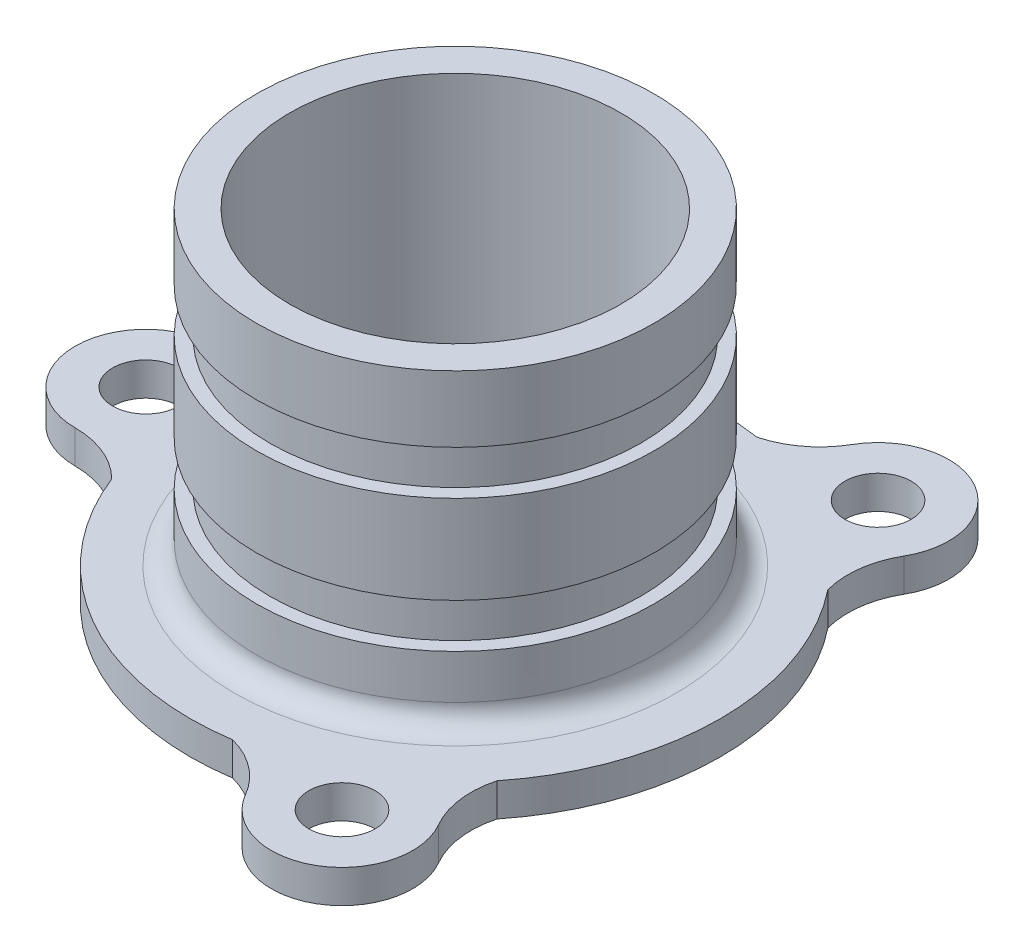
SolidWorks part; units mm, degrees
ref_plane "Front Plane" through (0, 0, 0) normal (0, 0, 1) x (1, 0, 0)
ref_plane "Top Plane" through (0, 0, 0) normal (0, 1, 0) x (1, 0, 0)
ref_plane "Right Plane" through (0, 0, 0) normal (1, 0, 0) x (0, 0, -1)
sketch "Sketch2" plane through (0, 0, 0) normal (0, 1, 0) x (1, 0, 0)
  line L1 (-70.05, 0) -> (161.6147, 0) construction
  line L2 (0, 87.4418) -> (0, -104.1606) construction
  circle A0 centre (0, 0) radius 37.5
  arc A1 (8.9547, 59.328) -> (-55.8569, 21.909) centre (0, 0) ccw
  circle A3 centre (-70.05, 0) radius 7.5
  arc A4 (-70.05, 16) -> (-70.05, -16) centre (-70.05, 0) ccw
  arc A5 (-70.05, -16) -> (-55.8569, -21.909) centre (-70.05, -36) cw
  arc A6 (-70.05, 16) -> (-55.8569, 21.909) centre (-70.05, 36) ccw
  arc A7 (48.8814, 52.6651) -> (21.1686, 68.6651) centre (35.025, 60.6651) ccw
  circle A8 centre (35.025, 60.6651) radius 7.5
  arc A9 (21.1686, 68.6651) -> (8.9547, 59.328) centre (3.8481, 78.6651) cw
  arc A10 (48.8814, 52.6651) -> (46.9022, 37.419) centre (66.2019, 42.6651) ccw
  arc A11 (21.1686, -68.6651) -> (48.8814, -52.6651) centre (35.025, -60.6651) ccw
  circle A12 centre (35.025, -60.6651) radius 7.5
  arc A13 (48.8814, -52.6651) -> (46.9022, -37.419) centre (66.2019, -42.6651) cw
  arc A14 (21.1686, -68.6651) -> (8.9547, -59.328) centre (3.8481, -78.6651) ccw
  arc A15 (46.9022, -37.419) -> (46.9022, 37.419) centre (0, 0) ccw
  arc A16 (-55.8569, -21.909) -> (8.9547, -59.328) centre (0, 0) ccw
  point P34 (0, 0)
  dimension "D1" = 75
  dimension "D2" = 120
  dimension "D3" = 3
  dimension "D4" = 15
  dimension "D5" = 32
  dimension "D6" = 20
  dimension "D7" = 20
extrude "Boss-Extrude1" add sketch "Sketch2" along normal blind 7.5
sketch "Sketch3" plane through (0, 7.5, 0) normal (0, 1, 0) x (1, 0, 0)
  circle A0 centre (0, 0) radius 37.5 construction
  circle A1 centre (0, 0) radius 37.5
  circle A2 centre (0, 0) radius 45
  arc A14 (-55.8569, -21.909) -> (-70.05, -16) centre (-70.05, -36) ccw
  arc A15 (-55.8569, -21.909) -> (8.9547, -59.328) centre (0, 0) ccw
  arc A16 (21.1686, -68.6651) -> (8.9547, -59.328) centre (3.8481, -78.6651) ccw
  arc A17 (21.1686, -68.6651) -> (48.8814, -52.6651) centre (35.025, -60.6651) ccw
  arc A18 (46.9022, -37.419) -> (48.8814, -52.6651) centre (66.2019, -42.6651) ccw
  arc A19 (46.9022, -37.419) -> (46.9022, 37.419) centre (0, 0) ccw
  arc A20 (48.8814, 52.6651) -> (46.9022, 37.419) centre (66.2019, 42.6651) ccw
  arc A21 (48.8814, 52.6651) -> (21.1686, 68.6651) centre (35.025, 60.6651) ccw
  arc A22 (8.9547, 59.328) -> (21.1686, 68.6651) centre (3.8481, 78.6651) ccw
  arc A23 (8.9547, 59.328) -> (-55.8569, 21.909) centre (0, 0) ccw
  arc A24 (-70.05, 16) -> (-55.8569, 21.909) centre (-70.05, 36) ccw
  arc A25 (-70.05, 16) -> (-70.05, -16) centre (-70.05, 0) ccw
  arc A26 (-55.8569, -21.909) -> (-70.05, -16) centre (-70.05, -36) ccw
  arc A27 (-55.8569, -21.909) -> (8.9547, -59.328) centre (0, 0) ccw
  arc A28 (21.1686, -68.6651) -> (8.9547, -59.328) centre (3.8481, -78.6651) ccw
  arc A29 (21.1686, -68.6651) -> (48.8814, -52.6651) centre (35.025, -60.6651) ccw
  arc A30 (46.9022, -37.419) -> (48.8814, -52.6651) centre (66.2019, -42.6651) ccw
  arc A31 (46.9022, -37.419) -> (46.9022, 37.419) centre (0, 0) ccw
  arc A32 (48.8814, 52.6651) -> (46.9022, 37.419) centre (66.2019, 42.6651) ccw
  arc A33 (48.8814, 52.6651) -> (21.1686, 68.6651) centre (35.025, 60.6651) ccw
  arc A34 (8.9547, 59.328) -> (21.1686, 68.6651) centre (3.8481, 78.6651) ccw
  arc A35 (8.9547, 59.328) -> (-55.8569, 21.909) centre (0, 0) ccw
  arc A36 (-70.05, 16) -> (-55.8569, 21.909) centre (-70.05, 36) ccw
  arc A37 (-70.05, 16) -> (-70.05, -16) centre (-70.05, 0) ccw
  circle M26 centre (0, 0) radius 37.5
  dimension "D2" = 90
  dimension "D1" = 0
extrude "Boss-Extrude2" add sketch "Sketch3" along normal blind 15 contours A2 M26
sketch "Sketch4" plane through (0, 22.5, 0) normal (0, 1, 0) x (1, 0, 0)
  circle A0 centre (0, 0) radius 42
  circle A1 centre (0, 0) radius 37.5
  dimension "D2" = 84
extrude "Boss-Extrude3" add sketch "Sketch4" along normal blind 10
sketch "Sketch5" plane through (0, 32.5, 0) normal (0, 1, 0) x (1, 0, 0)
  circle A1 centre (0, 0) radius 37.5
  circle A4 centre (0, 0) radius 42
  circle A5 centre (0, 0) radius 42
  circle A6 centre (0, 0) radius 45
  circle M3 centre (0, 0) radius 42
  circle M4 centre (0, 0) radius 37.5
  dimension "D3" = 90
  dimension "D2" = 0
extrude "Boss-Extrude4" add sketch "Sketch5" along normal blind 20 contours M3 M4 | A6 M3
sketch "Sketch6" plane through (0, 52.5, 0) normal (0, 1, 0) x (1, 0, 0)
  circle A1 centre (0, 0) radius 37.5
  circle A3 centre (0, 0) radius 42
  dimension "D1" = 84
extrude "Boss-Extrude5" add sketch "Sketch6" along normal blind 10
sketch "Sketch7" plane through (0, 62.5, 0) normal (0, 1, 0) x (1, 0, 0)
  circle A0 centre (0, 0) radius 37.5
  circle A3 centre (0, 0) radius 45
  dimension "D2" = 90
extrude "Boss-Extrude6" add sketch "Sketch7" along normal blind 15
fillet "Fillet1" radius 5 1 edges at (0, 7.5, -45)
